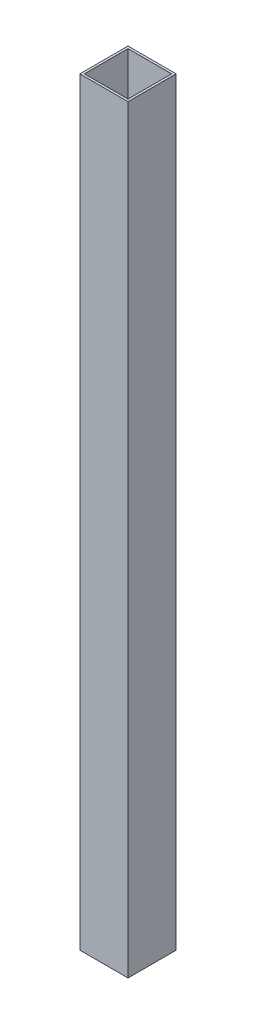
SolidWorks part; units mm, degrees
ref_plane "Front Plane" through (0, 0, 0) normal (0, 0, 1) x (1, 0, 0)
ref_plane "Top Plane" through (0, 0, 0) normal (0, 1, 0) x (1, 0, 0)
ref_plane "Right Plane" through (0, 0, 0) normal (1, 0, 0) x (0, 0, -1)
sketch "Sketch2" plane through (0, 0, 0) normal (0, 1, 0) x (1, 0, 0)
  line L0 (-11.5, 11.5) -> (11.5, 11.5)
  line L1 (-12.7, -12.7) -> (12.7, -12.7)
  line L2 (-12.7, -12.7) -> (-12.7, 12.7)
  line L3 (-12.7, 12.7) -> (12.7, 12.7)
  line L4 (12.7, -12.7) -> (12.7, 12.7)
  line L5 (-12.7, -12.7) -> (12.7, 12.7) construction
  line L6 (-12.7, 12.7) -> (12.7, -12.7) construction
  line L7 (11.5, -11.5) -> (11.5, 11.5)
  line L8 (-11.5, -11.5) -> (11.5, -11.5)
  line L9 (-11.5, -11.5) -> (-11.5, 11.5)
  point P0 (0, 0)
  dimension "D1" = 25.4
  dimension "D3" = 1.2
extrude "Boss-Extrude1" add sketch "Sketch2" along normal blind 400
